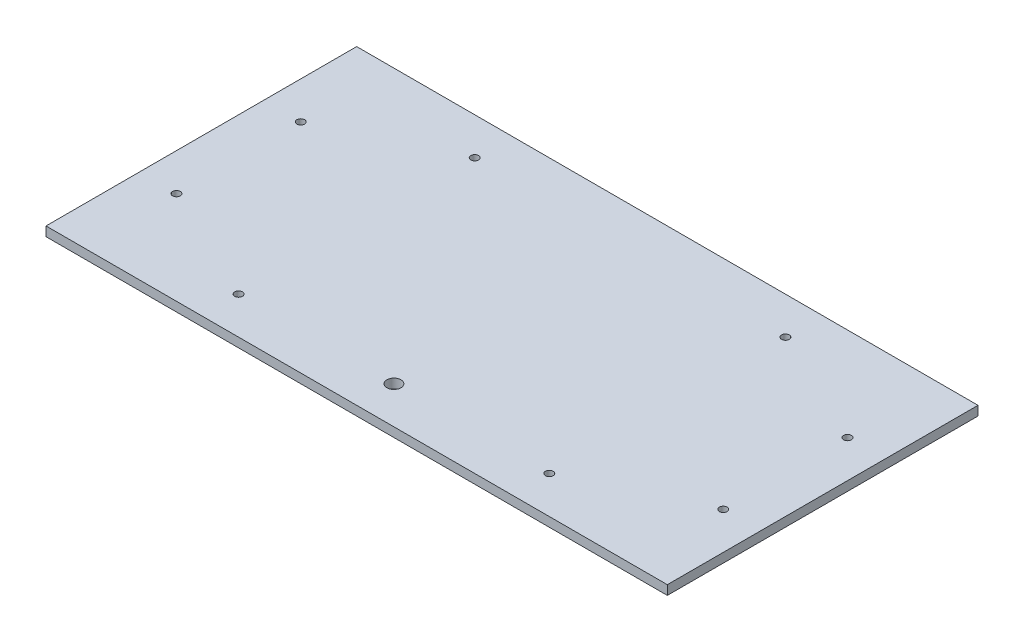
SolidWorks part; units mm, degrees
ref_plane "Plan de face" through (0, 0, 0) normal (0, 0, 1) x (1, 0, 0)
ref_plane "Plan de dessus" through (0, 0, 0) normal (0, 1, 0) x (1, 0, 0)
ref_plane "Plan de droite" through (0, 0, 0) normal (1, 0, 0) x (0, 0, -1)
sketch "Esquisse1" plane through (0, 0, 0) normal (0, 1, 0) x (1, 0, 0)
  line L1 (-200, -100) -> (200, -100)
  line L2 (-200, -100) -> (-200, 100)
  line L3 (-200, 100) -> (200, 100)
  line L4 (200, -100) -> (200, 100)
  line L5 (-200, -100) -> (200, 100) construction
  line L6 (-200, 100) -> (200, -100) construction
  point P0 (0, 0)
  dimension "D1" = 400
  dimension "D2" = 200
extrude "Boss.-Extru.1" add sketch "Esquisse1" along normal blind 6
sketch "Esquisse2" plane through (0, 6, 0) normal (0, 1, 0) x (1, 0, 0)
  line L0 (0, 100) -> (0, -100) construction
  line L1 (200, 100) -> (-200, 100) construction
  line L2 (-200, -100) -> (200, -100) construction
  line L3 (-200, 0) -> (200, 0) construction
  line L4 (-200, 100) -> (-200, -100) construction
  line L5 (200, -100) -> (200, 100) construction
  line L7 (-176, -76) -> (176, -76) construction
  line L8 (-176, -76) -> (-176, 76) construction
  line L9 (-176, 76) -> (176, 76) construction
  line L10 (176, -76) -> (176, 76) construction
  line L11 (-176, -76) -> (176, 76) construction
  line L12 (-176, 76) -> (176, -76) construction
  circle A0 centre (-100, 76) radius 2.5
  circle A1 centre (100, 76) radius 2.5
  circle A2 centre (100, -76) radius 2.5
  circle A3 centre (-100, -76) radius 2.5
  circle A4 centre (-176, 40) radius 2.5
  circle A5 centre (-176, -40) radius 2.5
  circle A6 centre (176, -40) radius 2.5
  circle A7 centre (176, 40) radius 2.5
  point P12 (0, 0)
  dimension "D3" = 5
  dimension "D1" = 24
  dimension "D2" = 24
  dimension "D4" = 200
  dimension "D5" = 80
extrude "Enlèv. mat.-Extru.1" cut sketch "Esquisse2" against normal through all
chamfer "Chanfrein1" [suppressed] distance 2 angle 45
sketch "Esquisse3" plane through (0, 6, 0) normal (0, 1, 0) x (1, 0, 0)
  line L0 (-100, -76) -> (100, -76) construction
  circle A0 centre (0, -76) radius 4.5
  dimension "D1" = 9
extrude "Enlèv. mat.-Extru.2" cut sketch "Esquisse3" against normal through all
